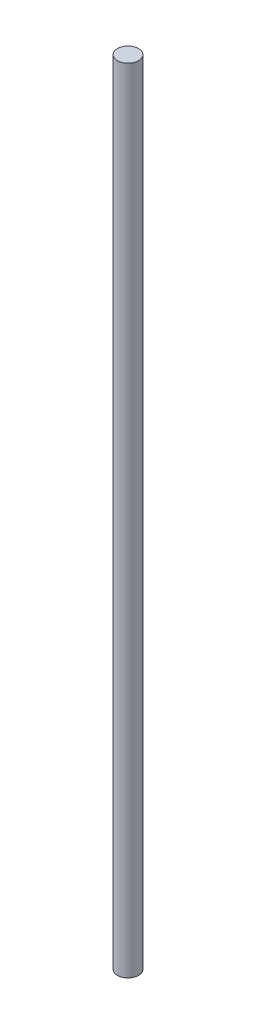
SolidWorks part; units mm, degrees
ref_plane "Front Plane" through (0, 0, 0) normal (0, 0, 1) x (1, 0, 0)
ref_plane "Top Plane" through (0, 0, 0) normal (0, 1, 0) x (1, 0, 0)
ref_plane "Right Plane" through (0, 0, 0) normal (1, 0, 0) x (0, 0, -1)
other "Configuration Table"
sketch "Sketch1" plane through (0, 0, 0) normal (0, 1, 0) x (1, 0, 0)
  circle A0 centre (550, 400) radius 8
extrude "PACK_lineer_ray_D16_2" add sketch "Sketch1" along normal blind 600 from offset 300 separate body
